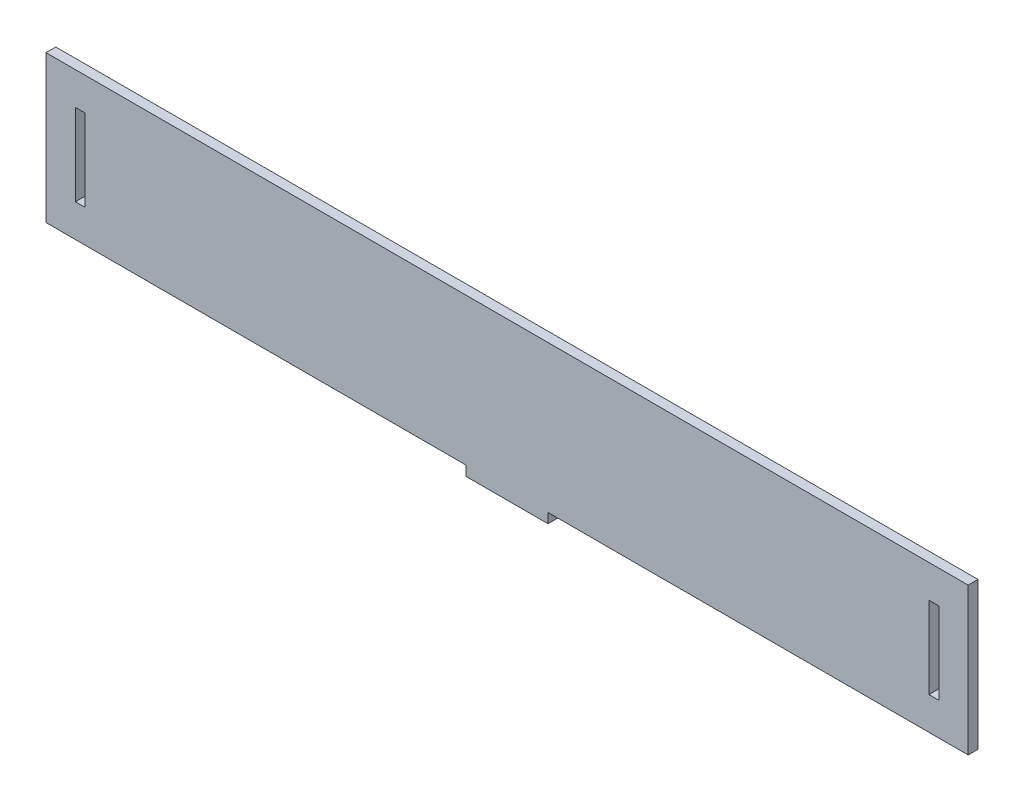
SolidWorks part; units mm, degrees
material "Maple"
ref_plane "Front Plane" through (0, 0, 0) normal (0, 0, 1) x (1, 0, 0)
ref_plane "Top Plane" through (0, 0, 0) normal (0, 1, 0) x (1, 0, 0)
ref_plane "Right Plane" through (0, 0, 0) normal (1, 0, 0) x (0, 0, -1)
sketch "Sketch1" plane through (0, 0, 0) normal (0, 0, 1) x (1, 0, 0)
  line L0 (282, 0) -> (282, -90) construction
  line L1 (0, 0) -> (564, 0)
  line L2 (0, 0) -> (0, -90)
  line L3 (0, -90) -> (257, -90)
  line L4 (564, 0) -> (564, -90)
  line L5 (564, -45) -> (0, -45) construction
  line L6 (307, -90) -> (564, -90)
  line L8 (257, -90) -> (257, -96)
  line L9 (257, -96) -> (307, -96)
  line L10 (307, -90) -> (307, -96)
  line L11 (546, -70) -> (540, -70)
  line L12 (18, -20) -> (24, -20)
  line L13 (18, -20) -> (18, -70)
  line L14 (18, -70) -> (24, -70)
  line L15 (24, -20) -> (24, -70)
  line L16 (18, -20) -> (24, -70) construction
  line L17 (18, -70) -> (24, -20) construction
  line L18 (540, -20) -> (540, -70)
  line L19 (546, -20) -> (540, -20)
  line L20 (546, -20) -> (546, -70)
  point P10 (21, -45)
  dimension "D1" = 564
  dimension "D2" = 90
  dimension "D3" = 50
  dimension "D4" = 6
  dimension "D5" = 50
  dimension "D6" = 18
  dimension "D7" = 6
extrude "Boss-Extrude1" add sketch "Sketch1" along normal blind 6
